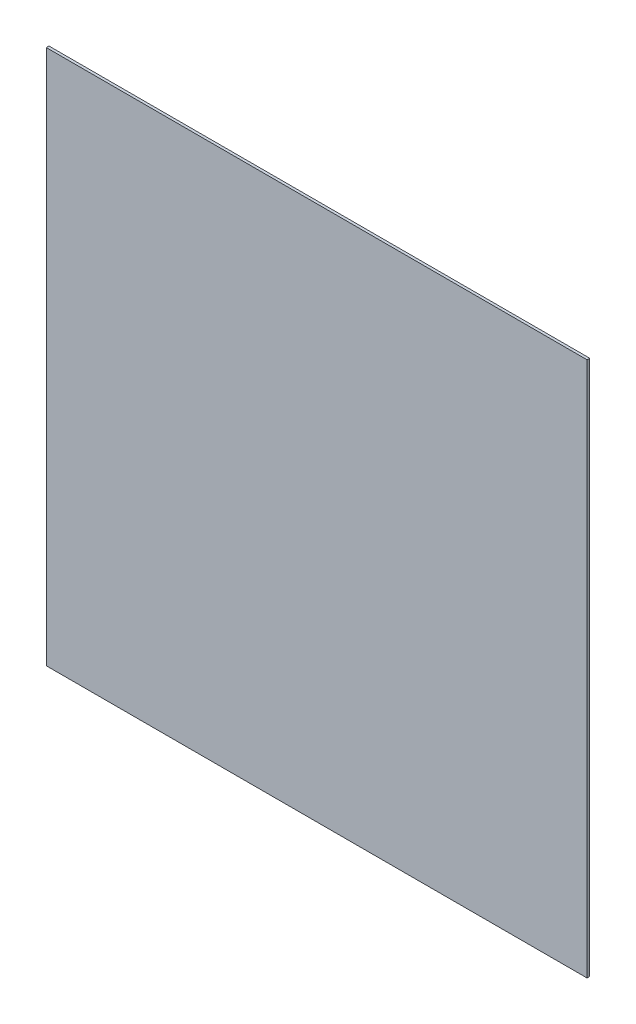
SolidWorks part; units mm, degrees
ref_plane "Front Plane" through (0, 0, 0) normal (0, 0, 1) x (1, 0, 0)
ref_plane "Top Plane" through (0, 0, 0) normal (0, 1, 0) x (1, 0, 0)
ref_plane "Right Plane" through (0, 0, 0) normal (1, 0, 0) x (0, 0, -1)
sketch "Sketch1" plane through (0, 0, 0) normal (0, 0, 1) x (1, 0, 0)
  line L1 (1005, -1008) -> (-5, -1008)
  line L2 (1005, -1008) -> (1005, -8)
  line L3 (1005, -8) -> (-5, -8)
  line L4 (-5, -1008) -> (-5, -8)
  line L5 (1005, -1008) -> (-5, -8) construction
  line L6 (1005, -8) -> (-5, -1008) construction
  point P0 (500, -508)
extrude "Extrude1" add sketch "Sketch1" along normal blind 5
